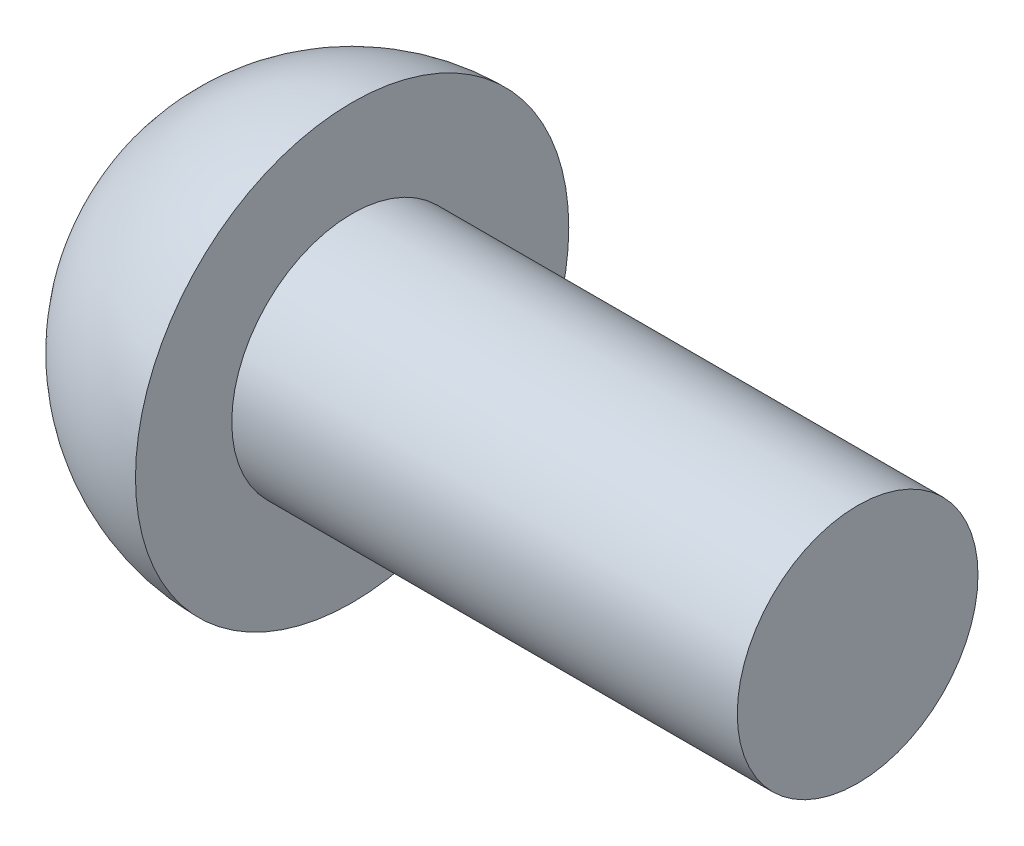
SolidWorks part; units mm, degrees
ref_plane "Front Plane" through (0, 0, 0) normal (0, 0, 1) x (1, 0, 0)
ref_plane "Top Plane" through (0, 0, 0) normal (0, 1, 0) x (1, 0, 0)
ref_plane "Right Plane" through (0, 0, 0) normal (1, 0, 0) x (0, 0, -1)
sketch "Sketch2" plane through (0, 0, 0) normal (0, 0, 1) x (1, 0, 0)
  line L0 (0, 0) -> (-21, 0)
  line L1 (-21, 0) -> (-21, 4)
  line L2 (-30, -5) -> (0, -5)
  line L4 (0, 0) -> (0, -5)
  arc A0 (-21, 4) -> (-30, -5) centre (-21, -5) ccw
  dimension "D1" = 21
  dimension "D2" = 4
revolve "Revolve1" add sketch "Sketch2" angle 360 about L2
